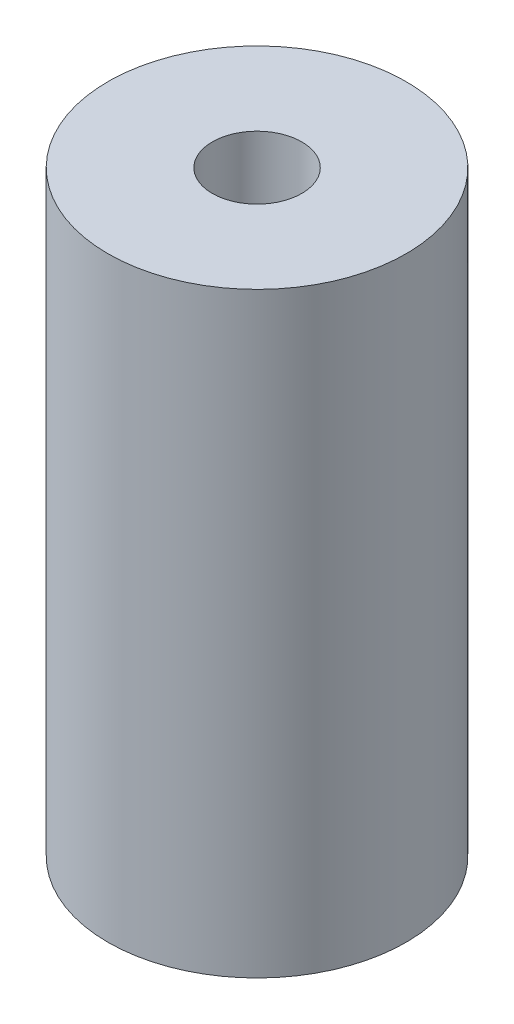
SolidWorks part; units mm, degrees
material "Galvanized Steel"
ref_plane "Alzado" through (0, 0, 0) normal (0, 0, 1) x (1, 0, 0)
ref_plane "Planta" through (0, 0, 0) normal (0, 1, 0) x (1, 0, 0)
ref_plane "Vista lateral" through (0, 0, 0) normal (1, 0, 0) x (0, 0, -1)
sketch "Sketch1" plane through (0, 0, 0) normal (0, 1, 0) x (1, 0, 0)
  circle A0 centre (0, 0) radius 5
  circle A1 centre (0, 0) radius 1.5
  dimension "D1" = 10
  dimension "D2" = 3
extrude "Boss-Extrude1" add sketch "Sketch1" along normal blind 20
